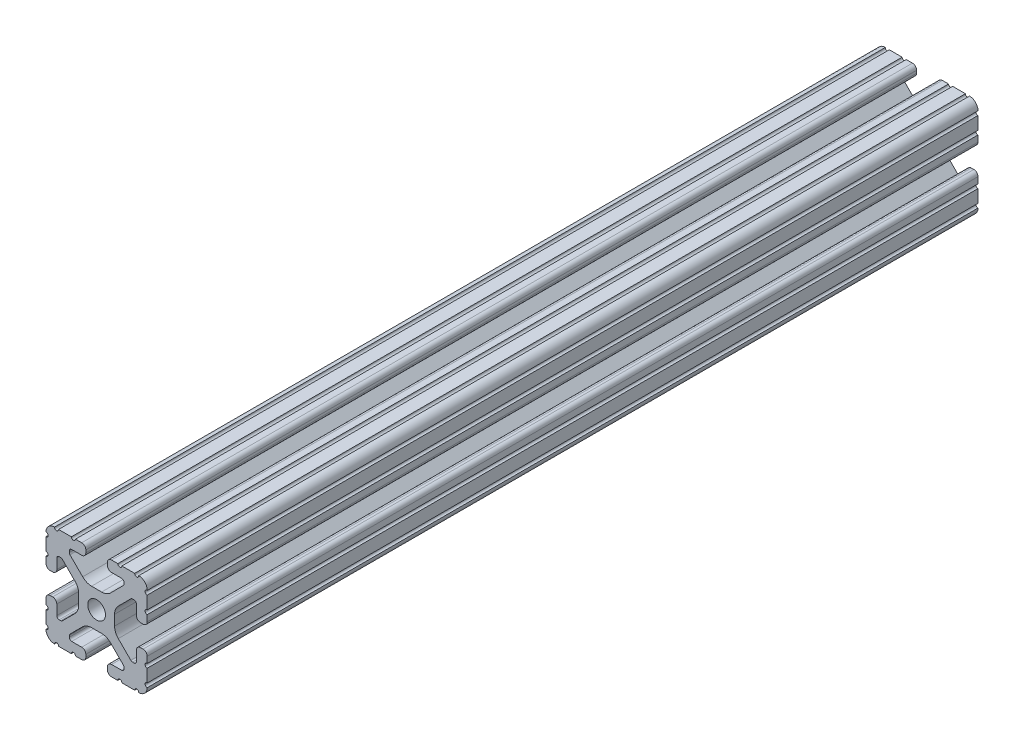
SolidWorks part; units mm, degrees
material "6061 Alloy"
ref_plane "Front Plane" through (0, 0, 0) normal (0, 0, 1) x (1, 0, 0)
ref_plane "Top Plane" through (0, 0, 0) normal (0, 1, 0) x (1, 0, 0)
ref_plane "Right Plane" through (0, 0, 0) normal (1, 0, 0) x (0, 0, -1)
sketch "Sketch1" plane through (0, 0, 0) normal (0, 0, 1) x (1, 0, 0)
  line L0 (0, 25.6181) -> (0, -24.623) construction
  line L1 (-20.8943, 0) -> (20.4607, 0) construction
  line L2 (-10.0229, 12.9148) -> (-5.2522, 8.144)
  line L3 (-10.287, 14.0843) -> (-10.287, 13.5524)
  line L4 (-5.6176, 14.986) -> (-9.3853, 14.986)
  line L5 (-4.064, 17.4964) -> (-4.064, 16.5396)
  line L6 (-7.9742, 19.05) -> (-5.6176, 19.05)
  line L7 (-14.3277, 19.05) -> (-9.4982, 19.05)
  line L8 (-19.05, 9.4961) -> (-19.05, 14.3277)
  line L9 (-19.05, 5.6176) -> (-19.05, 7.9763)
  line L10 (-16.5396, 4.064) -> (-17.4964, 4.064)
  line L11 (-14.986, 9.3853) -> (-14.986, 5.6176)
  line L12 (-13.516, 10.287) -> (-14.0843, 10.287)
  line L13 (-8.1476, 5.2921) -> (-12.8784, 10.0229)
  line L14 (-6.7564, -1.9335) -> (-6.7564, 1.9335)
  line L15 (-12.8784, -10.0229) -> (-8.1476, -5.2921)
  line L16 (-14.0843, -10.287) -> (-13.516, -10.287)
  line L17 (-14.986, -5.6176) -> (-14.986, -9.3853)
  line L18 (-17.4964, -4.064) -> (-16.5396, -4.064)
  line L19 (-19.05, -7.9763) -> (-19.05, -5.6176)
  line L20 (-19.05, -14.3277) -> (-19.05, -9.4961)
  line L21 (-9.4961, -19.05) -> (-14.3277, -19.05)
  line L22 (-5.6176, -19.05) -> (-7.9763, -19.05)
  line L23 (-4.064, -17.4964) -> (-4.064, -16.5396)
  line L24 (10.0229, -12.9148) -> (5.2522, -8.144)
  line L25 (10.287, -14.0843) -> (10.287, -13.5524)
  line L26 (5.6176, -14.986) -> (9.3853, -14.986)
  line L28 (-1.9022, 6.7564) -> (1.9022, 6.7564)
  line L29 (-1.9022, -6.7564) -> (1.9022, -6.7564)
  line L31 (-5.6176, -14.986) -> (-9.3853, -14.986)
  line L32 (-10.287, -14.0843) -> (-10.287, -13.5524)
  line L33 (-10.0229, -12.9148) -> (-5.2522, -8.144)
  line L66 (4.064, -16.5396) -> (4.064, -17.4964)
  line L67 (5.6176, -19.05) -> (7.9763, -19.05)
  line L68 (9.4961, -19.05) -> (14.3277, -19.05)
  line L69 (19.05, -14.3277) -> (19.05, -9.4961)
  line L70 (19.05, -7.9763) -> (19.05, -5.6176)
  line L71 (17.4964, -4.064) -> (16.5396, -4.064)
  line L72 (14.986, -5.6176) -> (14.986, -9.3853)
  line L73 (14.0843, -10.287) -> (13.516, -10.287)
  line L74 (12.8784, -10.0229) -> (8.1476, -5.2921)
  line L75 (6.7564, -1.9335) -> (6.7564, 1.9335)
  line L76 (8.1476, 5.2921) -> (12.8784, 10.0229)
  line L77 (13.516, 10.287) -> (14.0843, 10.287)
  line L78 (14.986, 9.3853) -> (14.986, 5.6176)
  line L79 (16.5396, 4.064) -> (17.4964, 4.064)
  line L80 (19.05, 5.6176) -> (19.05, 7.9763)
  line L81 (19.05, 9.4961) -> (19.05, 14.3277)
  line L82 (14.3277, 19.05) -> (9.4982, 19.05)
  line L83 (7.9742, 19.05) -> (5.6176, 19.05)
  line L84 (4.064, 17.4964) -> (4.064, 16.5396)
  line L85 (5.6176, 14.986) -> (9.3853, 14.986)
  line L86 (10.287, 14.0843) -> (10.287, 13.5524)
  line L87 (10.0229, 12.9148) -> (5.2522, 8.144)
  arc A0 (-10.0229, 12.9148) -> (-10.287, 13.5524) centre (-9.3853, 13.5524) cw
  circle A1 centre (0, 0) radius 3.3274
  arc A2 (-10.287, 14.0843) -> (-9.3853, 14.986) centre (-9.3853, 14.0843) cw
  arc A3 (-4.064, 16.5396) -> (-5.6176, 14.986) centre (-5.6176, 16.5396) cw
  arc A4 (-5.6176, 19.05) -> (-4.064, 17.4964) centre (-5.6176, 17.4964) cw
  arc A5 (-7.9742, 19.05) -> (-9.4982, 19.05) centre (-8.7362, 19.05) cw
  arc A6 (-14.3277, 19.05) -> (-15.8475, 19.05) centre (-15.0876, 18.9933) cw
  arc A7 (-19.05, 15.8475) -> (-15.8475, 19.05) centre (-15.8751, 15.8751) cw
  arc A8 (-19.05, 15.8475) -> (-19.05, 14.3277) centre (-18.9933, 15.0876) cw
  arc A9 (-19.05, 9.4961) -> (-19.05, 7.9763) centre (-18.9933, 8.7362) cw
  arc A10 (-17.4964, 4.064) -> (-19.05, 5.6176) centre (-17.4964, 5.6176) cw
  arc A11 (-14.986, 5.6176) -> (-16.5396, 4.064) centre (-16.5396, 5.6176) cw
  arc A12 (-14.986, 9.3853) -> (-14.0843, 10.287) centre (-14.0843, 9.3853) cw
  arc A13 (-13.516, 10.287) -> (-12.8784, 10.0229) centre (-13.516, 9.3853) cw
  arc A14 (-8.1476, 5.2921) -> (-6.7564, 1.9335) centre (-11.5062, 1.9335) cw
  arc A15 (-6.7564, -1.9335) -> (-8.1476, -5.2921) centre (-11.5062, -1.9335) cw
  arc A16 (-12.8784, -10.0229) -> (-13.516, -10.287) centre (-13.516, -9.3853) cw
  arc A17 (-14.0843, -10.287) -> (-14.986, -9.3853) centre (-14.0843, -9.3853) cw
  arc A18 (-16.5396, -4.064) -> (-14.986, -5.6176) centre (-16.5396, -5.6176) cw
  arc A19 (-19.05, -5.6176) -> (-17.4964, -4.064) centre (-17.4964, -5.6176) cw
  arc A20 (-19.05, -7.9763) -> (-19.05, -9.4961) centre (-18.9933, -8.7362) cw
  arc A21 (-19.05, -14.3277) -> (-19.05, -15.8475) centre (-18.9933, -15.0876) cw
  arc A22 (-15.8475, -19.05) -> (-19.05, -15.8475) centre (-15.8751, -15.8751) cw
  arc A23 (-15.8475, -19.05) -> (-14.3277, -19.05) centre (-15.0876, -18.9933) cw
  arc A24 (-9.4961, -19.05) -> (-7.9763, -19.05) centre (-8.7362, -18.9933) cw
  arc A25 (-4.064, -17.4964) -> (-5.6176, -19.05) centre (-5.6176, -17.4964) cw
  arc A26 (-5.2522, -8.144) -> (-1.9022, -6.7564) centre (-1.9022, -11.494) cw
  arc A27 (1.9022, -6.7564) -> (5.2522, -8.144) centre (1.9022, -11.494) cw
  arc A28 (10.0229, -12.9148) -> (10.287, -13.5524) centre (9.3853, -13.5524) cw
  arc A29 (10.287, -14.0843) -> (9.3853, -14.986) centre (9.3853, -14.0843) cw
  arc A30 (4.064, -16.5396) -> (5.6176, -14.986) centre (5.6176, -16.5396) cw
  arc A31 (-4.064, -16.5396) -> (-5.6176, -14.986) centre (-5.6176, -16.5396) ccw
  arc A32 (-10.287, -14.0843) -> (-9.3853, -14.986) centre (-9.3853, -14.0843) ccw
  arc A33 (-10.0229, -12.9148) -> (-10.287, -13.5524) centre (-9.3853, -13.5524) ccw
  arc A79 (4.064, -17.4964) -> (5.6176, -19.05) centre (5.6176, -17.4964) ccw
  arc A80 (9.4961, -19.05) -> (7.9763, -19.05) centre (8.7362, -18.9933) ccw
  arc A81 (15.8475, -19.05) -> (14.3277, -19.05) centre (15.0876, -18.9933) ccw
  arc A82 (15.8475, -19.05) -> (19.05, -15.8475) centre (15.8751, -15.8751) ccw
  arc A83 (19.05, -14.3277) -> (19.05, -15.8475) centre (18.9933, -15.0876) ccw
  arc A84 (19.05, -7.9763) -> (19.05, -9.4961) centre (18.9933, -8.7362) ccw
  arc A85 (19.05, -5.6176) -> (17.4964, -4.064) centre (17.4964, -5.6176) ccw
  arc A86 (16.5396, -4.064) -> (14.986, -5.6176) centre (16.5396, -5.6176) ccw
  arc A87 (14.0843, -10.287) -> (14.986, -9.3853) centre (14.0843, -9.3853) ccw
  arc A88 (12.8784, -10.0229) -> (13.516, -10.287) centre (13.516, -9.3853) ccw
  arc A89 (6.7564, -1.9335) -> (8.1476, -5.2921) centre (11.5062, -1.9335) ccw
  arc A90 (8.1476, 5.2921) -> (6.7564, 1.9335) centre (11.5062, 1.9335) ccw
  arc A91 (13.516, 10.287) -> (12.8784, 10.0229) centre (13.516, 9.3853) ccw
  arc A92 (14.986, 9.3853) -> (14.0843, 10.287) centre (14.0843, 9.3853) ccw
  arc A93 (14.986, 5.6176) -> (16.5396, 4.064) centre (16.5396, 5.6176) ccw
  arc A94 (17.4964, 4.064) -> (19.05, 5.6176) centre (17.4964, 5.6176) ccw
  arc A95 (19.05, 9.4961) -> (19.05, 7.9763) centre (18.9933, 8.7362) ccw
  arc A96 (19.05, 15.8475) -> (19.05, 14.3277) centre (18.9933, 15.0876) ccw
  arc A97 (19.05, 15.8475) -> (15.8475, 19.05) centre (15.8751, 15.8751) ccw
  arc A98 (14.3277, 19.05) -> (15.8475, 19.05) centre (15.0876, 18.9933) ccw
  arc A99 (7.9742, 19.05) -> (9.4982, 19.05) centre (8.7362, 19.05) ccw
  arc A100 (5.6176, 19.05) -> (4.064, 17.4964) centre (5.6176, 17.4964) ccw
  arc A101 (4.064, 16.5396) -> (5.6176, 14.986) centre (5.6176, 16.5396) ccw
  arc A102 (10.287, 14.0843) -> (9.3853, 14.986) centre (9.3853, 14.0843) ccw
  arc A103 (10.0229, 12.9148) -> (10.287, 13.5524) centre (9.3853, 13.5524) ccw
  arc A104 (1.9022, 6.7564) -> (5.2522, 8.144) centre (1.9022, 11.494) ccw
  arc A105 (-5.2522, 8.144) -> (-1.9022, 6.7564) centre (-1.9022, 11.494) ccw
  dimension "D1" = 6.6548
  dimension "D2" = 19.05
  dimension "D3" = 38.1
  dimension "D4" = 20.574
  dimension "D5" = 13.5128
  dimension "D6" = 4.064
  dimension "D7" = 8.128
  dimension "D8" = 4.064
  dimension "D9" = 12.2936
extrude "Extrude1" add sketch "Sketch1" against normal blind 312.7
